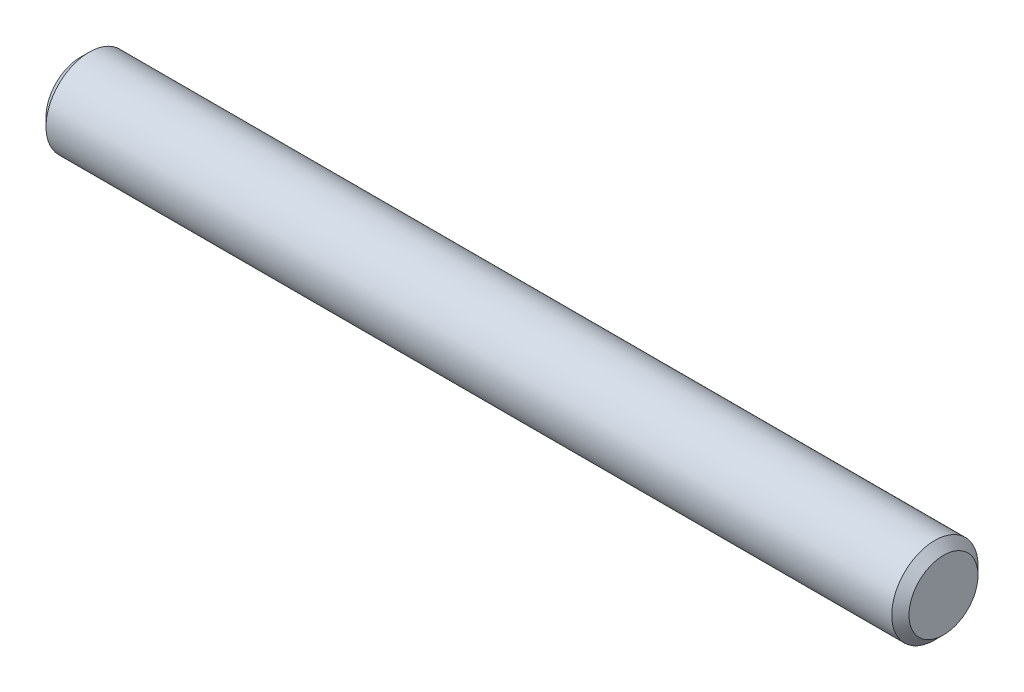
SolidWorks part; units mm, degrees
ref_plane "Front" through (0, 0, 0) normal (0, 0, 1) x (1, 0, 0)
ref_plane "Top" through (0, 0, 0) normal (0, 1, 0) x (1, 0, 0)
ref_plane "Right" through (0, 0, 0) normal (1, 0, 0) x (0, 0, -1)
sketch "Sketch1" plane through (0, 0, 0) normal (0, 0, 1) x (1, 0, 0)
  line L0 (-3.9688, 0) -> (3.9688, 0) construction
  line L1 (3.9687, 0.3969) -> (3.9687, -0.3969) construction
  line L2 (-3.9688, 0.3969) -> (-3.9688, -0.3969) construction
  dimension "Length" = 7.9375
  dimension "Diameter" = 0.7937
sketch "Sketch2" plane through (0, 0, 0) normal (1, 0, 0) x (0, 0, -1)
  circle A0 centre (0, 0) radius 0.3969
extrude "Extrude1" add sketch "Sketch2" against normal up to vertex (3.9688 mm away) and the other way up to vertex (3.9688 mm away) up to point (-3.9688, 0.3969, 0) other way up to point (3.9687, 0.3969, 0)
chamfer "Chamfer1" distance 0.0794 angle 45 2 edges at (3.9687, 0, -0.3969) (-3.9688, 0, -0.3969)
equation "\"D1@Chamfer1\" = \"Diameter@Sketch1\"*.1"
